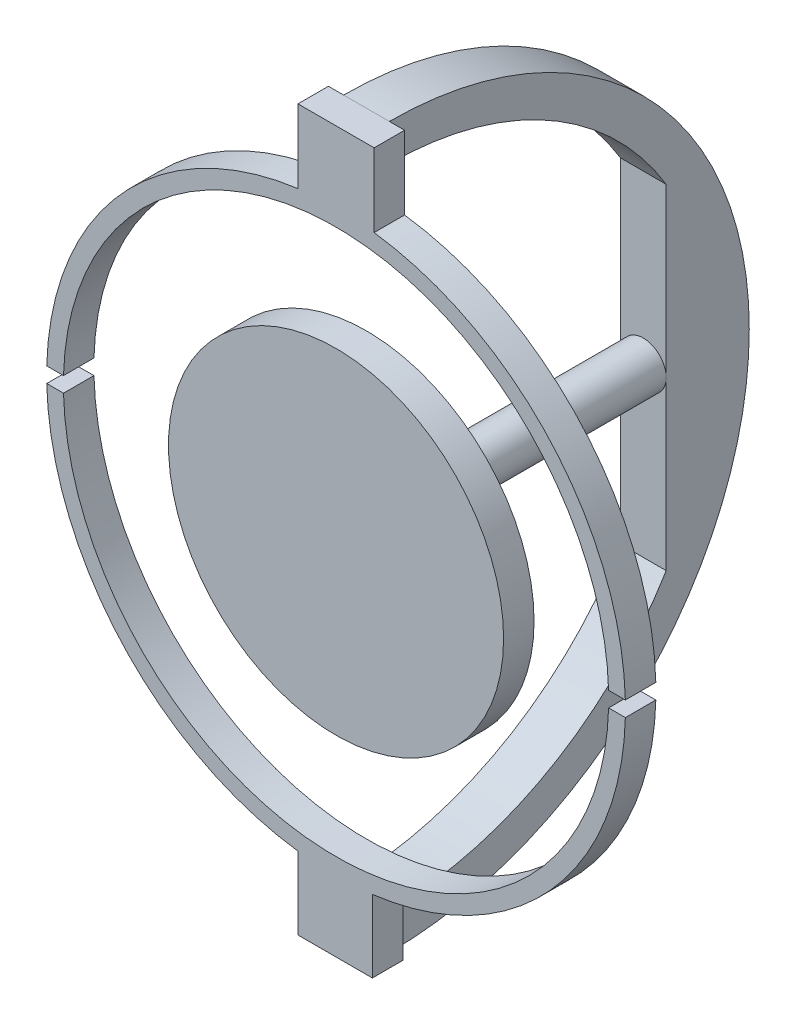
SolidWorks part; units mm, degrees
ref_plane "Front Plane" through (0, 0, 0) normal (0, 0, 1) x (1, 0, 0)
ref_plane "Top Plane" through (0, 0, 0) normal (0, 1, 0) x (1, 0, 0)
ref_plane "Right Plane" through (0, 0, 0) normal (1, 0, 0) x (0, 0, -1)
sketch "Sketch1" plane through (0, 0, 0) normal (0, 0, 1) x (1, 0, 0)
  line L33 (-19.4529, 0.5073) -> (19.5471, 0.5073)
  line L34 (-19.4529, 0.5073) -> (-19.4529, -0.4927)
  line L35 (-19.4529, -0.4927) -> (19.5471, -0.4927)
  line L36 (19.5471, 0.5073) -> (19.5471, -0.4927)
  line L37 (-2.5, 18.6537) -> (2.5, 18.6537)
  line L38 (-2.5, 18.6537) -> (-2.5, 23.6537)
  line L39 (-2.5, 23.6537) -> (2.5, 23.6537)
  line L40 (2.5, 18.6537) -> (2.5, 23.6537)
  line L41 (-2.5, -23.6036) -> (2.3841, -23.6036)
  line L42 (-2.5, -23.6036) -> (-2.5, -18.6036)
  line L43 (-2.5, -18.6036) -> (2.3841, -18.6036)
  line L44 (2.3841, -23.6036) -> (2.3841, -18.6036)
  circle A0 centre (0, 0) radius 19
  circle A1 centre (0, 0) radius 17.9
  circle A2 centre (0, 0) radius 11
  dimension "D1" = 38
  dimension "D2" = 35.8
  dimension "D3" = 22
  dimension "D4" = 5
  dimension "D10" = 39
  dimension "D11" = 1
  dimension "D12" = 5
  dimension "D13" = 5
extrude "Boss-Extrude10" add sketch "Sketch1" along normal blind 2 contours L40 A0 L38 L37 | A0 L40 L39 L38 | A1 L33 A0 L40 L37 L38 | A1 L35 A0 L42 L43 L44 | L35 A2 | L33 A2 L35 | L33 A2 | A0 L42 L41 L44 | L42 A0 L44 L43
sketch "Sketch7" plane through (0, 0, 0) normal (1, 0, 0) x (0, 0, -1)
  line L0 (0, 18.8348) -> (0, 23.6537) construction
  line L1 (0, -23.6036) -> (0, -18.8498) construction
  line L2 (18.1749, 10.9915) -> (18.1749, -10.974)
  line L3 (0, 23.6537) -> (0, 21.2443)
  line L4 (0, -21.2267) -> (0, -23.6036)
  arc A0 (0, 23.6537) -> (0, -23.6036) centre (0, 0.025) cw
  arc A1 (0, 21.2443) -> (0, -21.2267) centre (0, 0.0088) cw
  arc A2 (18.1749, 10.9915) -> (18.1749, -10.974) centre (0, 0.0088) cw
extrude "Boss-Extrude11" add sketch "Sketch7" along normal mid plane 3 contours A1 L4 A0 L3 | A1 L2
sketch "Sketch8" plane through (0, 0, 0) normal (0, 0, 1) x (1, 0, 0)
  circle A0 centre (0, 0) radius 1.5
extrude "Boss-Extrude12" add sketch "Sketch8" against normal blind 21
